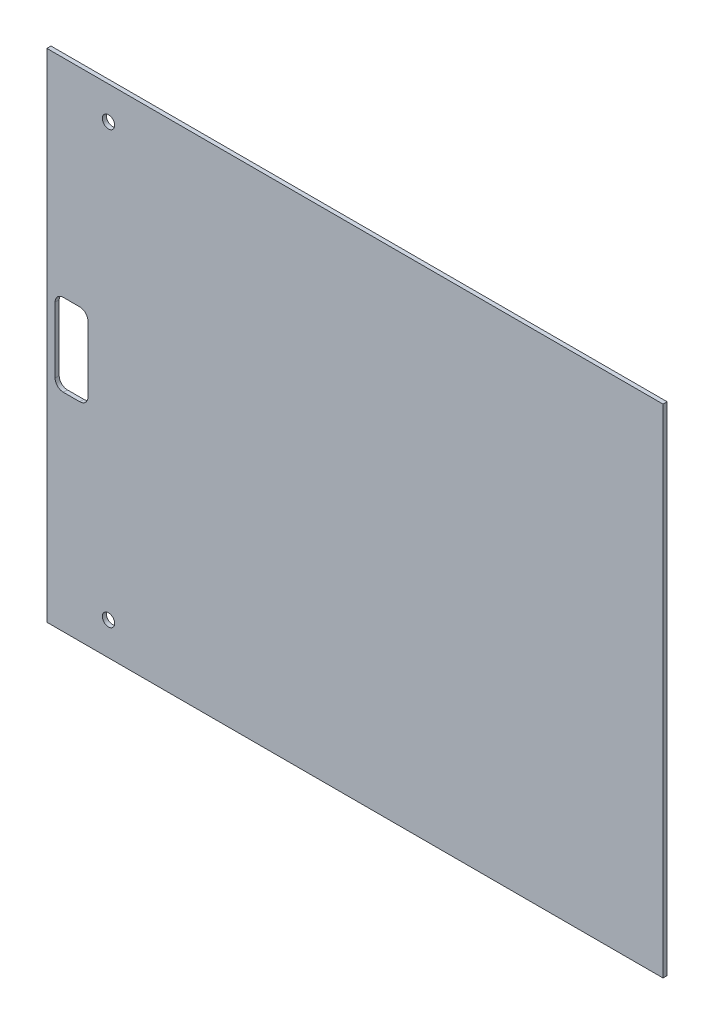
SolidWorks part; units mm, degrees
ref_plane "前视基准面" through (0, 0, 0) normal (0, 0, 1) x (1, 0, 0)
ref_plane "上视基准面" through (0, 0, 0) normal (0, 1, 0) x (1, 0, 0)
ref_plane "右视基准面" through (0, 0, 0) normal (1, 0, 0) x (0, 0, -1)
sketch "草图1" plane through (0, 0, 0) normal (0, 0, 1) x (1, 0, 0)
  line L1 (-75, 60.5) -> (75, 60.5)
  line L2 (-75, 60.5) -> (-75, -60.5)
  line L3 (-75, -60.5) -> (75, -60.5)
  line L4 (75, 60.5) -> (75, -60.5)
  line L5 (-75, 60.5) -> (75, -60.5) construction
  line L6 (-75, -60.5) -> (75, 60.5) construction
  line L7 (-71, 10) -> (-67, 10)
  line L8 (-73, 8) -> (-73, -8)
  line L9 (-71, -10) -> (-67, -10)
  line L10 (-65, 8) -> (-65, -8)
  line L11 (-73, 10) -> (-65, -10) construction
  line L12 (-73, -10) -> (-65, 10) construction
  circle A0 centre (-60, 52.5) radius 1.5
  circle A1 centre (-60, -52.5) radius 1.5
  arc A2 (-67, -10) -> (-65, -8) centre (-67, -8) ccw
  arc A3 (-73, -8) -> (-71, -10) centre (-71, -8) ccw
  arc A4 (-71, 10) -> (-73, 8) centre (-71, 8) ccw
  arc A5 (-67, 10) -> (-65, 8) centre (-67, 8) cw
  point P0 (0, 0)
  point P10 (-69, 0)
  dimension "D3" = 3
  dimension "D6" = 8
  dimension "D11" = 2
  dimension "D1" = 121
  dimension "D2" = 150
  dimension "D4" = 8
  dimension "D5" = 15
  dimension "D7" = 15
  dimension "D8" = 20
  dimension "D9" = 8
  dimension "D10" = 6
  dimension "D12" = 60.5
extrude "凸台-拉伸2" add sketch "草图1" along normal blind 1
